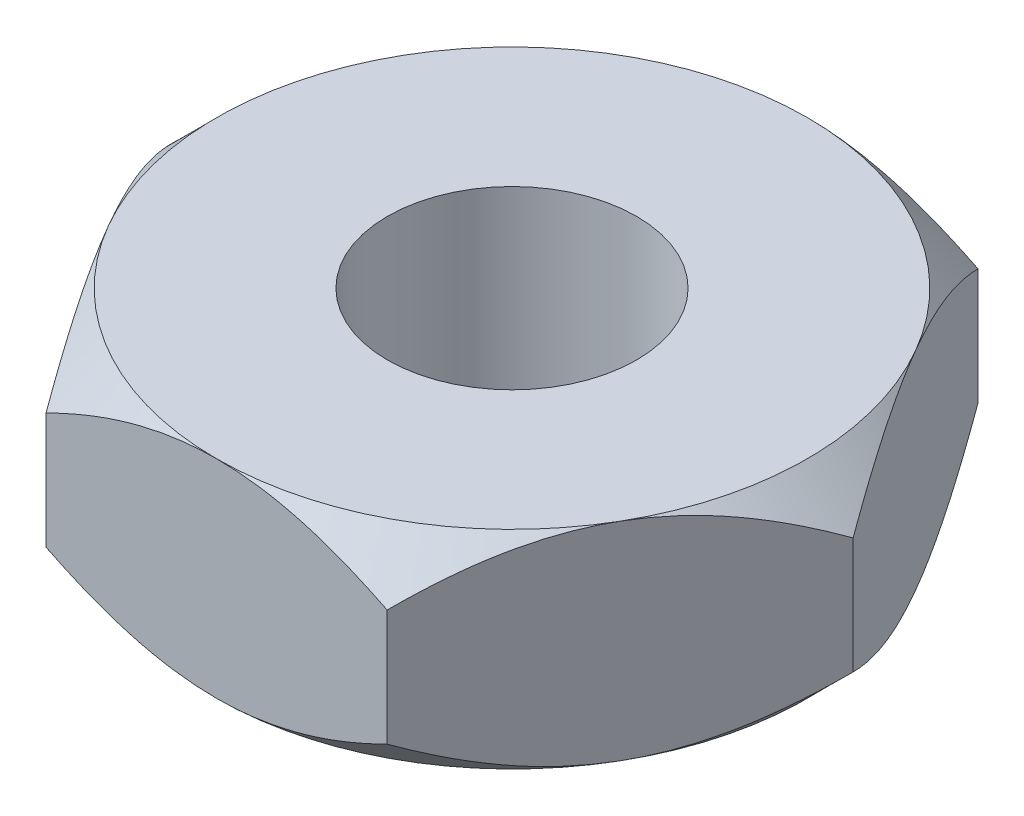
SolidWorks part; units mm, degrees
ref_plane "前视基准面" through (0, 0, 0) normal (0, 0, 1) x (1, 0, 0)
ref_plane "上视基准面" through (0, 0, 0) normal (0, 1, 0) x (1, 0, 0)
ref_plane "右视基准面" through (0, 0, 0) normal (1, 0, 0) x (0, 0, -1)
other "Configuration Table"
sketch "草图1" plane through (0, 0, 0) normal (0, 1, 0) x (1, 0, 0)
  line L1 (8.2179, 0) -> (4.1089, 7.1169)
  line L2 (4.1089, 7.1169) -> (-4.1089, 7.1169)
  line L3 (-4.1089, 7.1169) -> (-8.2179, 0)
  line L4 (-8.2179, 0) -> (-4.1089, -7.1169)
  line L5 (-4.1089, -7.1169) -> (4.1089, -7.1169)
  line L6 (4.1089, -7.1169) -> (8.2179, 0)
  circle A0 centre (0, 0) radius 7.1169 construction
  circle A2 centre (0, 0) radius 3
  dimension "D1" = 8.2179
  dimension "D2" = 6
  dimension "D3" = 7.1169
extrude "凸台-拉伸2" add sketch "草图1" along normal mid plane 5 contours A2 | L3 L4 L5 L6 L1 L2
sketch "草图4" plane through (0, 2.5, 0) normal (0, 1, 0) x (1, 0, 0)
  circle A0 centre (0, 0) radius 7.1169
extrude "切除-拉伸1" cut sketch "草图4" against normal through all draft 45 flip side to cut
sketch "草图5" plane through (0, -2.5, 0) normal (0, -1, 0) x (1, 0, 0)
  circle A0 centre (0, 0) radius 7.1169
extrude "切除-拉伸2" cut sketch "草图5" against normal through all draft 45 flip side to cut
